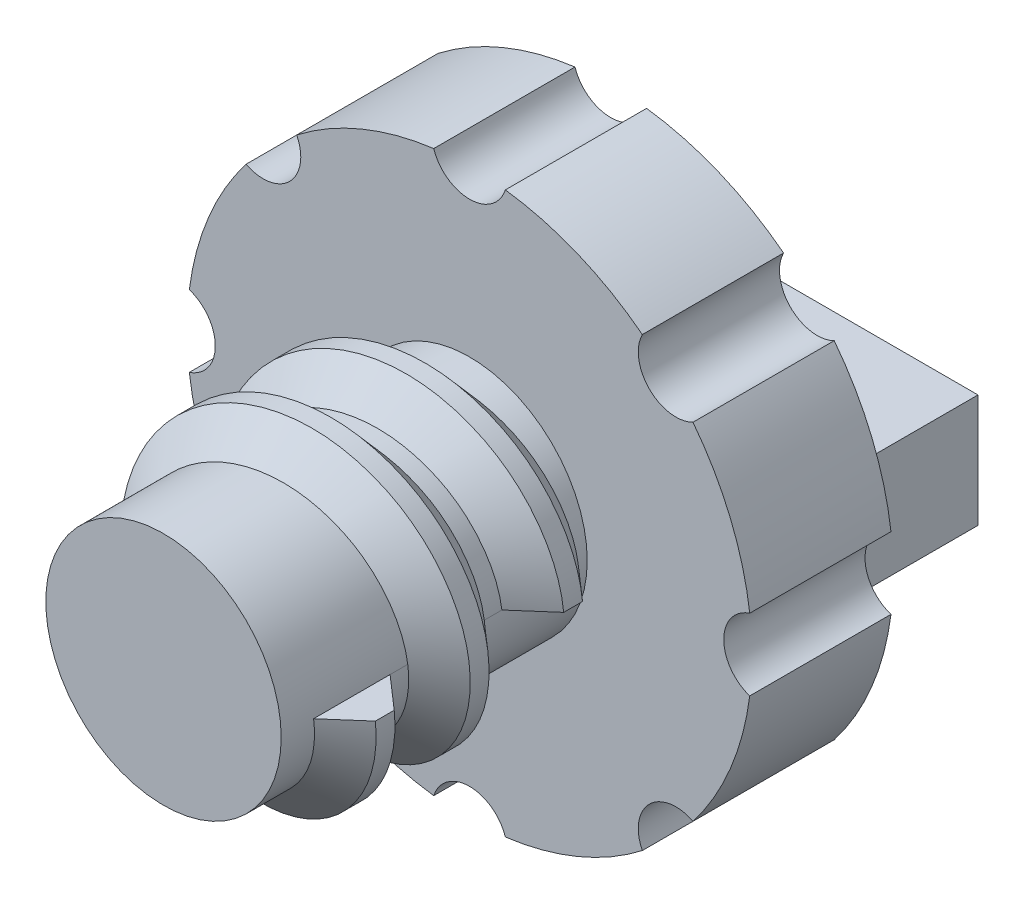
SolidWorks part; units mm, degrees
ref_plane "Front Plane" through (0, 0, 0) normal (0, 0, 1) x (1, 0, 0)
ref_plane "Top Plane" through (0, 0, 0) normal (0, 1, 0) x (1, 0, 0)
ref_plane "Right Plane" through (0, 0, 0) normal (1, 0, 0) x (0, 0, -1)
sketch "Sketch1" plane through (0, 0, 0) normal (0, 0, 1) x (1, 0, 0)
  circle A0 centre (0, 0) radius 6
extrude "Finger_grip_head_D12" add sketch "Sketch1" along normal blind 3 from offset 3
sketch "Sketch2" plane through (0, 0, 0) normal (0, 0, 1) x (1, 0, 0)
  circle A0 centre (0, 0) radius 2.5
extrude "Core_D5" add sketch "Sketch2" along normal blind 6.5 from offset 0
ref_plane "Coarse_thread_D6p4_P2_start_plane" through (0, 0, 1) normal (0, 0, 1) x (1, 0, 0)
sketch "Sketch3" plane through (0, 0, 1) normal (0, 0, 1) x (1, 0, 0)
  circle A0 centre (0, 0) radius 2.45
curve "Coarse_thread_D6p4_P2_helix" pitch 2 height 4 turns 2
sketch3d "3DSketch1"
  line L0 (2.4, 0, 0.1) -> (3.2, 0, 0.8)
  line L1 (3.2, 0, 0.8) -> (3.2, 0, 1.2)
  line L2 (3.2, 0, 1.2) -> (2.4, 0, 1.9)
  line L3 (2.4, 0, 1.9) -> (2.4, 0, 0.1)
sweep "Coarse_thread_D6p4_P2" add profiles "3DSketch1" path "Coarse_thread_D6p4_P2_helix"
sketch "Sketch4" plane through (0, 0, 0) normal (0, 0, 1) x (1, 0, 0)
  circle A0 centre (6.2, 0) radius 0.8
  circle A1 centre (4.3841, 4.3841) radius 0.8
  circle A2 centre (0, 6.2) radius 0.8
  circle A3 centre (-4.3841, 4.3841) radius 0.8
  circle A4 centre (-6.2, 0) radius 0.8
  circle A5 centre (-4.3841, -4.3841) radius 0.8
  circle A6 centre (0, -6.2) radius 0.8
  circle A7 centre (4.3841, -4.3841) radius 0.8
extrude "Finger_grip_flutes" cut sketch "Sketch4" along normal blind 3 from offset 3
sketch "Sketch5" plane through (0, 0, 0) normal (0, 0, 1) x (1, 0, 0)
  line L0 (-4.8, -1.2) -> (4.8, -1.2)
  line L1 (4.8, -1.2) -> (4.8, 1.2)
  line L2 (4.8, 1.2) -> (-4.8, 1.2)
  line L3 (-4.8, 1.2) -> (-4.8, -1.2)
extrude "Raised_finger_turning_grip" add sketch "Sketch5" along normal blind 3.1 from offset 6
